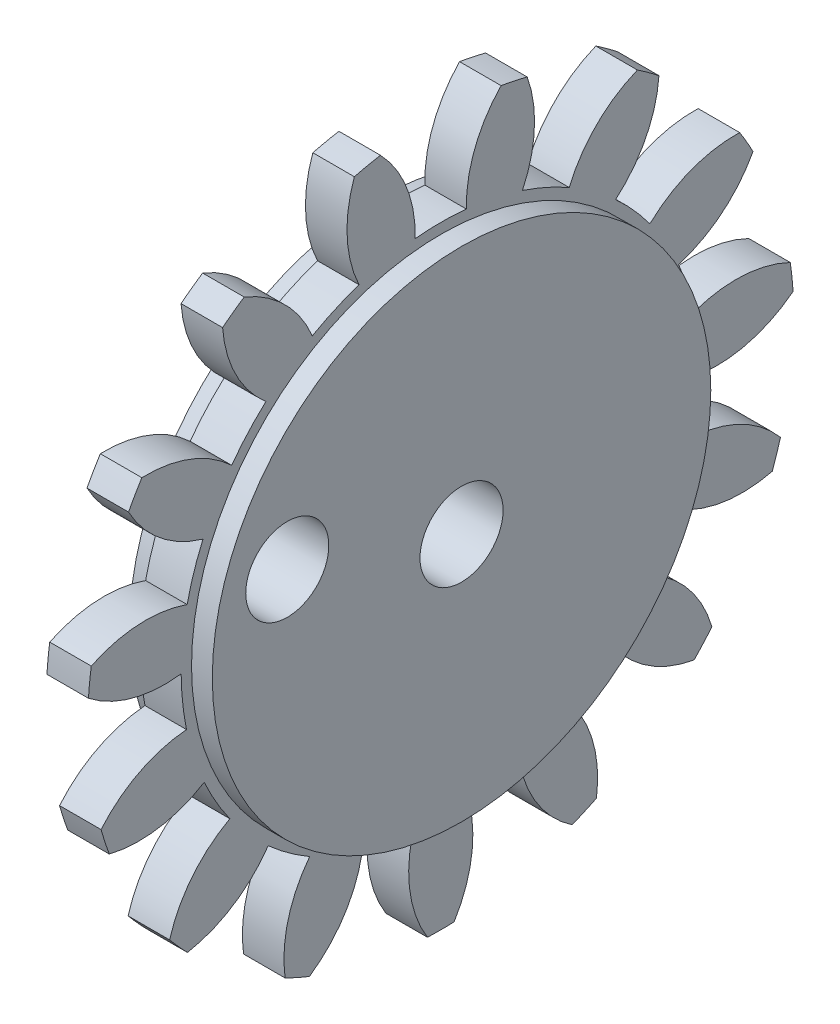
SolidWorks part; units mm, degrees
ref_plane "Plane1" through (0, 0, 0) normal (0, 0, 1) x (1, 0, 0)
ref_plane "Plane2" through (0, 0, 0) normal (0, 1, 0) x (1, 0, 0)
ref_plane "Plane3" through (0, 0, 0) normal (1, 0, 0) x (0, 0, -1)
other "Configuration Table"
sketch "HoldingSke" plane through (0, 0, 0) normal (0, 1, 0) x (1, 0, 0)
  line L0 (0, 0) -> (98.1381, -26.296)
  line L1 (-15, 0) -> (100, 0) construction
  line L2 (0, 0) -> (-2.1039, 2.3779)
  line L3 (0, 0) -> (-11.863, 4.5341)
  line L4 (0, 0) -> (8.3417, 2.2352)
  line L5 (0, 0) -> (-11.8993, -4.4381)
  line L6 (0, 0) -> (-5.2639, -3.5516)
  line L7 (-2.1039, 2.3779) -> (0.6298, 14.7802)
  line L8 (-76.2, 54.61) -> (-61.976, 54.61)
  line L9 (-67.7845, 28.3722) -> (-49.3413, 33.142)
  line L10 (-76.2, 71.12) -> (104.1128, 71.12)
  line L11 (0, 0) -> (-6.35, 0)
  line L12 (-76.2, 101.6) -> (-75.9714, 101.6)
  line L13 (24.9733, 27.94) -> (52.9518, 28.4284)
  line L14 (24.9733, 27.94) -> (24.9746, 27.94)
  line L15 (24.9733, 27.94) -> (100.4006, 29.5858)
  circle A0 centre (0, 0) radius 6.35
  circle A1 centre (0, 0) radius 38.1
  circle A2 centre (0, 0) radius 38.1
  circle A3 centre (0, 0) radius 6.35
  dimension "MHD" = 76.2
  dimension "Hub_dia" = 76.2
  dimension "Bore" = 12.7
  dimension "MBD" = 12.7
  dimension "Num_teeth" = 15
  dimension "Pitch" = 101.6
  dimension "Overall_len" = 12.7
  dimension "Show_teeth" = 15
  dimension "Thickness" = 6.35
  dimension "OAL" = 12.7001
  dimension "T_dim" = 14.224
  dimension "Ap" = 14.5
  dimension "H" = 19.05
  dimension "Pitch_radius" = 180.3128
  dimension "Width" = 6.35
  dimension "Backlash" = 0.2286
  dimension "Addendum_fac" = 1
  dimension "Dedendum_fac" = 1.25
  dimension "Clearance_fac" = 0.25
  dimension "Dedendum_add" = 0.0013
sketch "BasProSke" plane through (0, 0, 0) normal (0, 1, 0) x (1, 0, 0)
  line L0 (-10, 0) -> (60, 0) construction
  line L1 (0, 0) -> (0, 53.975)
  line L2 (0, 0) -> (6.35, 0)
  line L3 (6.35, 0) -> (6.35, 53.975)
  line L4 (6.35, 53.975) -> (0, 53.975)
  dimension "Thickness" = 6.35
  dimension "Diameter" = 107.95
revolve "Base-Revolve" add sketch "BasProSke" angle 360 about L0
sketch "TooCutSke" plane through (0, 0, 0) normal (1, 0, 0) x (0, 0, -1)
  line L1 (0, 0) -> (0, 107) construction
  line L2 (0, 0) -> (-5.3779, 47.3204) construction
  line L3 (0, 0) -> (-19.7119, 92.7371) construction
  line L4 (-5.3779, 47.3204) -> (-9.8559, 46.3685) construction
  arc A0 (3.9155, 39.4926) -> (-3.9155, 39.4926) centre (0, 0) ccw
  arc A1 (9.2414, 53.2038) -> (-9.2414, 53.2038) centre (0, 0) ccw
  circle A2 centre (0, 0) radius 47.625 construction
  circle A3 centre (0, 0) radius 46.108 construction
  arc A4 (-3.9155, 39.4926) -> (-9.2414, 53.2038) centre (-22.9591, 39.9854) ccw
  arc A5 (9.2414, 53.2038) -> (3.9155, 39.4926) centre (22.9591, 39.9854) ccw
  dimension "Root_dia" = 79.3725
  dimension "Overcut_dia" = 108.0008
  dimension "Pitch_dia" = 95.25
  dimension "Base_dia" = 92.2161
  dimension "Flank_rad" = 19.05
  dimension "Half_ang" = 12
  dimension "Half_CT" = 4.5781
extrude "ToothCut" cut sketch "TooCutSke" along normal through all
fillet "Breaks" [suppressed] radius 0.127
fillet "RootFillets" [suppressed] radius 1.5888
pattern_circular "TeethCuts" count 15 every 24 about axis through (-10, 0, 0) along (1, 0, 0) of "ToothCut", "RootFillets", "Breaks"
sketch "HubNeaOneSke" plane through (0, 0, 0) normal (-1, 0, 0) x (0, 0, 1)
  circle A0 centre (0, 0) radius 38.1
  dimension "Diameter" = 76.2
extrude "HubNearOne" [suppressed] add sketch "HubNeaOneSke" along normal blind 6.3501
sketch "HubNeaBotSke" plane through (0, 0, 0) normal (-1, 0, 0) x (0, 0, 1)
  circle A0 centre (0, 0) radius 38.1
  dimension "Diameter" = 76.2
extrude "HubNearBoth" add sketch "HubNeaBotSke" along normal blind 3.175
ref_plane "FarPln" through (6.35, 0, 0) normal (1, 0, 0) x (0, 0, -1)
sketch "HubFarSke" plane through (6.35, 0, 0) normal (1, 0, 0) x (0, 0, -1)
  circle A0 centre (0, 0) radius 38.1
  dimension "Diameter" = 76.2
extrude "HubFar" add sketch "HubFarSke" along normal blind 3.175
sketch "BorSke" plane through (0, 0, 0) normal (1, 0, 0) x (0, 0, -1)
  circle A0 centre (0, 0) radius 6.35
  dimension "Diameter" = 12.7
extrude "Bore" cut sketch "BorSke" along normal mid plane 25.4001
sketch "KeySke" plane through (0, 0, 0) normal (1, 0, 0) x (0, 0, -1)
  line L0 (-1.5875, 0) -> (-1.5875, 7.874)
  line L1 (-1.5875, 7.874) -> (1.5875, 7.874)
  line L2 (1.5875, 7.874) -> (1.5875, 0)
  line L3 (0, 0) -> (0, 34) construction
  line L4 (-1.5875, 0) -> (1.5875, 0)
  dimension "Offset" = 7.874
  dimension "Width" = 3.175
extrude "Keyway" [suppressed] cut sketch "KeySke" along normal mid plane 25.4001
pattern_circular "Keyway2" [suppressed] count 2 every 90 about axis through (-10, 0, 0) along (1, 0, 0)
sketch "Sketch1" plane through (-3.175, 0, 0) normal (-1, 0, 0) x (0, 0, 1)
  line L0 (0, 0) -> (27.6826, 4.2691) construction
  line L1 (0, 0) -> (46.7437, 26.9875) construction
  line L2 (0, 0) -> (37.7438, 12.2637) construction
  circle A0 centre (27.6826, 4.2691) radius 6.35 construction
  arc A1 (47.7296, 25.2029) -> (45.6911, 28.7336) centre (0, 0) ccw construction
  circle A2 centre (0, 0) radius 28.0098 construction
  arc A4 (38.7696, 8.48) -> (36.3498, 15.9277) centre (0, 0) ccw construction
  circle A5 centre (26.6389, 8.6555) radius 6.35
extrude "Cut-Extrude1" cut sketch "Sketch1" against normal through all
scale "Scale1" scale about centroid uniform scaling yes scale factor 0.75
equation "' \"Pitch@HoldingSke\" = 4"
equation "' \"Num_teeth@HoldingSke\" = 12"
equation "' \"Ap@HoldingSke\" =  20"
equation "' \"Ap@HoldingSke\" = 20"
equation "' \"Width@HoldingSke\" = 0.5"
equation "' \"Hub_dia@HoldingSke\"= 1"
equation "' \"Hub_dia@HoldingSke\" = 1"
equation "' \"Overall_len@HoldingSke\" = 1.0"
equation "' \"Bore@HoldingSke\" = 0.75"
equation "' \"T_dim@HoldingSke\" = 0.85"
equation "' \"Width@KeySke\" = 0.25"
equation "' \"Show_teeth@HoldingSke\" = 13"
equation "' \"Backlash@HoldingSke\" = 0.009"
equation "' \"Addendum_fac@HoldingSke\" = 1.0"
equation "' \"Dedendum_fac@HoldingSke\" = 1.25"
equation "' \"Dedendum_add@HoldingSke\" = 0.00005"
equation "' \"Clearance_fac@HoldingSke\" = 0.25"
equation "' \"Pitch@HoldingSke\" = 0.5"
equation "' \"Num_teeth@HoldingSke\" = 23"
equation "' \"Show_teeth@HoldingSke\" = 23"
equation "' \"Backlash@HoldingSke\" = 0.0375"
equation "\"Overcut_dia@TooCutSke\" = (\"Num_teeth@HoldingSke\" + 2 * \"Addendum_fac@HoldingSke\") / \"Pitch@HoldingSke\" + 0.002"
equation "\"Pitch_dia@TooCutSke\" = \"Num_teeth@HoldingSke\" / \"Pitch@HoldingSke\""
equation "\"Base_dia@TooCutSke\" = \"Num_teeth@HoldingSke\" / \"Pitch@HoldingSke\" * cos((\"Ap@HoldingSke\"  * 3.14159265 / 180))"
equation "\"Root_dia@TooCutSke\" = (\"Num_teeth@HoldingSke\" + 2) / \"Pitch@HoldingSke\" - 2 * (\"Addendum_fac@HoldingSke\" + \"Dedendum_fac@HoldingSke\") / \"Pitch@HoldingSke\" - \"Dedendum_add@HoldingSke\" * 2"
equation "\"Half_ang@TooCutSke\" = 180 / \"Num_teeth@HoldingSke\""
equation "\"Half_CT@TooCutSke\" = \"Num_teeth@HoldingSke\" / \"Pitch@HoldingSke\" * sin((3.14159265 / 2 / \"Num_teeth@HoldingSke\")) / 2 - 7 * \"Backlash@HoldingSke\" / 4"
equation "\"Flank_rad@TooCutSke\" = \"Num_teeth@HoldingSke\" / \"Pitch@HoldingSke\" / 5"
equation "\"Radius@RootFillets\" = \"Clearance_fac@HoldingSke\" / \"Pitch@HoldingSke\" + \"Dedendum_add@HoldingSke\""
equation "\"Break_rad@Breaks\" = 0.02 / \"Pitch@HoldingSke\""
equation "\"Thickness@HoldingSke\" = \"Width@HoldingSke\""
equation "\"OAL@HoldingSke\" = \"Thickness@HoldingSke\""
equation "\"MHD@HoldingSke\" = (\"Num_teeth@HoldingSke\" + 2) / \"Pitch@HoldingSke\" - 2 * (\"Addendum_fac@HoldingSke\" + \"Dedendum_fac@HoldingSke\")  / \"Pitch@HoldingSke\" - \"Dedendum_add@HoldingSke\" * 2"
equation "\"MBD@HoldingSke\" = (\"Num_teeth@HoldingSke\" + 2) / \"Pitch@HoldingSke\" - 2 * (\"Addendum_fac@HoldingSke\" + \"Dedendum_fac@HoldingSke\")  / \"Pitch@HoldingSke\" - \"Dedendum_add@HoldingSke\" * 2 - 0.002"
equation "\"MHD@HoldingSke\" = ((sgn( \"MHD@HoldingSke\" - \"Hub_dia@HoldingSke\" )-1)*( \"MHD@HoldingSke\" - \"Hub_dia@HoldingSke\" ))/-2+ \"Hub_dia@HoldingSke\""
equation "\"MBD@HoldingSke\" = ((sgn( \"MBD@HoldingSke\" - \"Bore@HoldingSke\" )-1)*( \"MBD@HoldingSke\" - \"Bore@HoldingSke\" ))/-2+ \"Bore@HoldingSke\""
equation "\"OAL@HoldingSke\" = ((sgn( \"OAL@HoldingSke\" - \"Overall_len@HoldingSke\" )+1)*( \"OAL@HoldingSke\" - \"Overall_len@HoldingSke\" ))/2 + \"Overall_len@HoldingSke\" + 0.000002"
equation "\"Num_teeth@TeethCuts\" = int( \"Show_teeth@HoldingSke\" ) + 1"
equation "\"Num_teeth@TeethCuts\" = ((sgn( \"Num_teeth@TeethCuts\" - \"Num_teeth@HoldingSke\" )-1)*( \"Num_teeth@TeethCuts\" - \"Num_teeth@HoldingSke\" ))/-2+ \"Num_teeth@HoldingSke\""
equation "\"Num_teeth@TeethCuts\" = ((sgn( \"Num_teeth@TeethCuts\" - 2.0)+1)*( \"Num_teeth@TeethCuts\" - 2.0))/2 +2.0"
equation "\"Angle@TeethCuts\" = 360.0 / \"Num_teeth@HoldingSke\""
equation "\"Diameter@BasProSke\" = (\"Num_teeth@HoldingSke\" + 2 * \"Addendum_fac@HoldingSke\") / \"Pitch@HoldingSke\""
equation "\"Thickness@BasProSke\"  = \"Thickness@HoldingSke\""
equation "' \"Fillet_rad@BasProSke\" =  \"Thickness@HoldingSke\" * 0.05"
equation "' \"Fillet_rad@BasProSke\" = \"Thickness@HoldingSke\" * 0.05"
equation "\"MHD@HoldingSke\" = ((sgn( \"MHD@HoldingSke\" - \"Root_dia@TooCutSke\" )-1)*( \"MHD@HoldingSke\" - \"Root_dia@TooCutSke\" ))/-2+ \"Root_dia@TooCutSke\""
equation "\"Diameter@HubNeaOneSke\" = \"MHD@HoldingSke\""
equation "\"Length@HubNearOne\" = \"OAL@HoldingSke\" - \"Thickness@BasProSke\""
equation "\"Diameter@HubNeaBotSke\" = \"MHD@HoldingSke\""
equation "\"Length@HubNearBoth\" = ( \"OAL@HoldingSke\" - \"Thickness@BasProSke\" ) / 2.0"
equation "\"Thickness@FarPln\" = \"Thickness@BasProSke\""
equation "\"Diameter@HubFarSke\" = \"MHD@HoldingSke\""
equation "\"Length@HubFar\" = ( \"OAL@HoldingSke\" - \"Thickness@BasProSke\" ) / 2.0"
equation "\"Diameter@BorSke\" = \"MBD@HoldingSke\""
equation "\"D1@Bore\" = \"OAL@HoldingSke\" * 2.0"
equation "\"D1@Keyway\" = \"OAL@HoldingSke\" * 2.0"
equation "\"Offset@KeySke\" = \"T_dim@HoldingSke\" - \"MBD@HoldingSke\" / 2.0"
